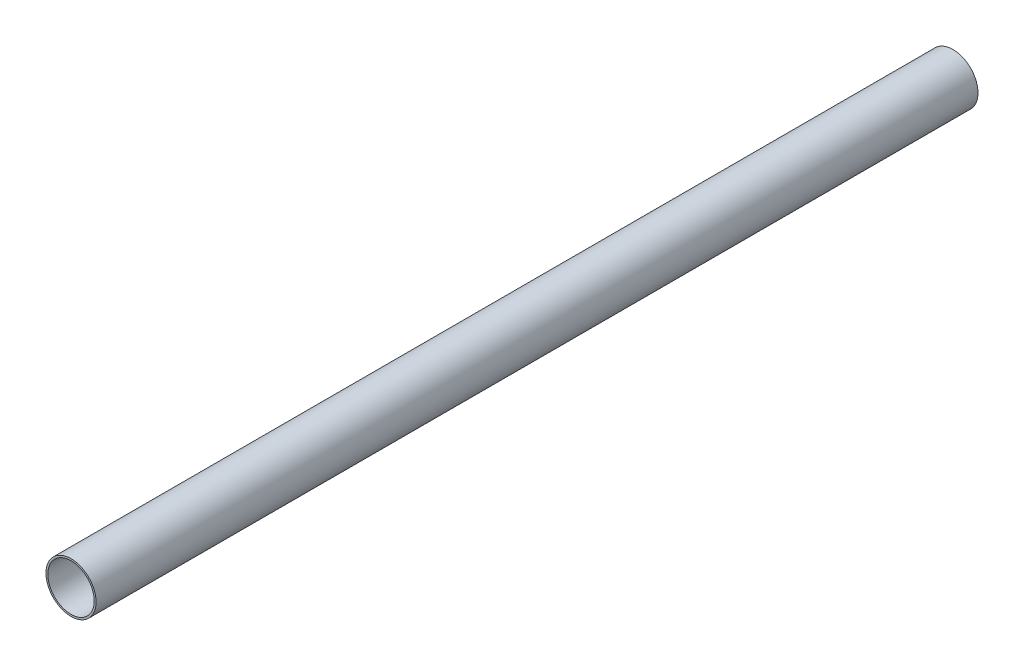
SolidWorks part; units mm, degrees
ref_plane "前视基准面" through (0, 0, 0) normal (0, 0, 1) x (1, 0, 0)
ref_plane "上视基准面" through (0, 0, 0) normal (0, 1, 0) x (1, 0, 0)
ref_plane "右视基准面" through (0, 0, 0) normal (1, 0, 0) x (0, 0, -1)
sketch "草图1" plane through (0, 0, 0) normal (1, 0, 0) x (0, 0, -1)
  line L0 (0, 0) -> (1900, 0)
  line L1 (55, 0) -> (-55, 0) construction
  dimension "D1" = 1900
other "普通钢管 108 X 4(1)"
ref_plane "基准面1" through (0, 0, 0) normal (0, 0, -1) x (0, 1, 0)
sketch "Sketch1" plane through (0, 0, 0) normal (0, 0, -1) x (0, 1, 0)
  circle A0 centre (0, 0) radius 50
  circle A1 centre (0, 0) radius 54
  point P3 (0, 54)
  point P5 (-54, 0)
  point P6 (0, -54)
  point P7 (54, 0)
  point P8 (0, 0)
  dimension "Out_dia" = 108
  dimension "D1" = 4
